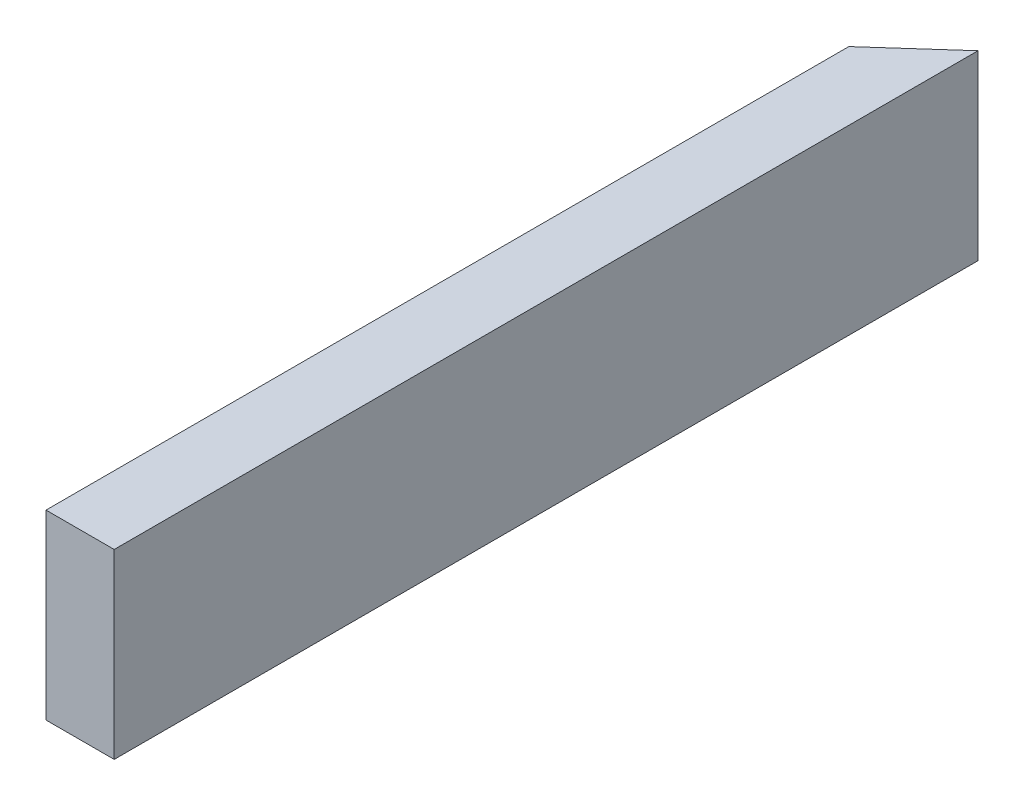
SolidWorks part; units mm, degrees
ref_plane "Front Plane" through (0, 0, 0) normal (0, 0, 1) x (1, 0, 0)
ref_plane "Top Plane" through (0, 0, 0) normal (0, 1, 0) x (1, 0, 0)
ref_plane "Right Plane" through (0, 0, 0) normal (1, 0, 0) x (0, 0, -1)
sketch "Sketch1" plane through (0, 0, 0) normal (0, 0, 1) x (1, 0, 0)
  line L1 (-3.9032, 12.8387) -> (-0.9032, 12.8387)
  line L2 (-3.9032, 12.8387) -> (-3.9032, 4.8387)
  line L3 (-3.9032, 4.8387) -> (-0.9032, 4.8387)
  line L4 (-0.9032, 12.8387) -> (-0.9032, 4.8387)
  dimension "D1" = 3
  dimension "D2" = 8
extrude "Boss-Extrude1" add sketch "Sketch1" along normal blind 38
ref_plane "Plane1" through (0, 12.8387, 0) normal (0, 1, 0) x (1, 0, 0)
sketch "Sketch3" plane through (0, 12.8387, 0) normal (0, 1, 0) x (1, 0, 0)
  line L0 (-0.9032, 0) -> (-3.9032, -2.6823)
  line L1 (-3.9032, -38) -> (-3.9032, 0) construction
  line L2 (-3.9032, -2.6823) -> (-3.9032, 0)
  line L3 (-3.9032, 0) -> (-0.9032, 0)
  dimension "D1" = 41.8
extrude "Cut-Extrude1" cut sketch "Sketch3" against normal blind 52
